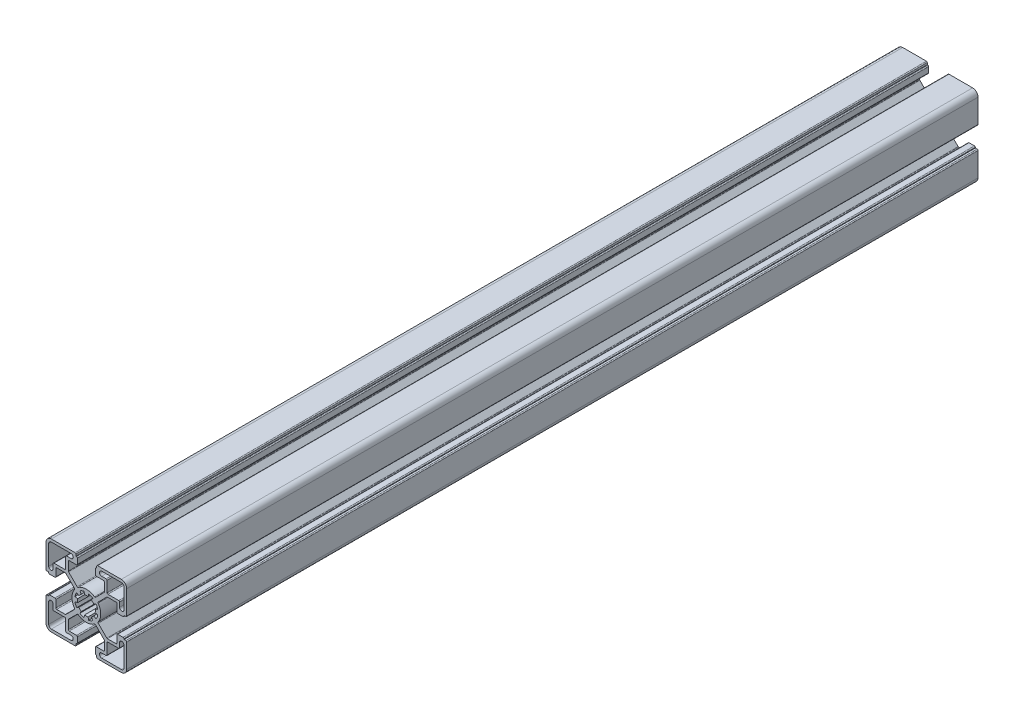
SolidWorks part; units mm, degrees
material "6063-O"
ref_plane "Front Plane" through (0, 0, 0) normal (0, 0, 1) x (1, 0, 0)
ref_plane "Top Plane" through (0, 0, 0) normal (0, 1, 0) x (1, 0, 0)
ref_plane "Right Plane" through (0, 0, 0) normal (1, 0, 0) x (0, 0, -1)
sketch "Sketch1" plane through (0, 0, 0) normal (0, 0, 1) x (1, 0, 0)
  line L0 (0, 22.5) -> (0, -22.5) construction
  line L1 (22.5, 0) -> (-22.5, 0) construction
  line L2 (-5.8, 22.5) -> (5.8, 22.5) construction
  line L3 (-5, 21) -> (5, 21) construction
  line L4 (-10.05, 10.05) -> (10.05, 10.05) construction
  line L5 (0, 0) -> (-10.05, 10.05) construction
  circle A0 centre (0, 0) radius 5 construction
  point P4 (0, 0)
  point P8 (0, 0)
  point P10 (0, 8)
  point P14 (0, 22.5)
  point P17 (0, 21)
  point P19 (0, 10.05)
sketch "Sketch2" plane through (0, 0, 0) normal (1, 0, 0) x (0, 0, -1)
  line L0 (152.4, 0) -> (-152.4, 0) construction
  point P4 (0, 0)
  dimension "D1" = 304.8
sketch "Sketch3" plane through (0, 0, 0) normal (0, 0, 1) x (1, 0, 0)
  line L5 (-21, 8.5375) -> (-21, 19.5)
  line L9 (0, 0) -> (-22.5, 22.5) construction
  line L10 (-11.55, -10.05) -> (-6.3569, -4.8569)
  line L11 (-19.5, 21) -> (-8.5375, 21)
  line L38 (-5.8, 22.5) -> (-5.8, 21)
  line L46 (-5.8, 21) -> (-5, 21)
  line L62 (-5, 21) -> (-5, 17.025)
  line L74 (-5, 17.025) -> (-10.05, 17.025)
  line L76 (-10.05, 17.025) -> (-10.05, 11.55)
  line L77 (-10.05, 11.55) -> (-4.8569, 6.3569)
  line L78 (-18.525, 8.5375) -> (-18.525, 11.55)
  line L79 (-10.05, 17.025) -> (-10.05, 22.5) construction
  line L80 (0, 22.5) -> (0, -22.5) construction
  line L81 (-5.8, 22.5) -> (5.8, 22.5) construction
  line L82 (10.05, 11.55) -> (4.8569, 6.3569)
  line L83 (10.05, 17.025) -> (10.05, 11.55)
  line L84 (5, 17.025) -> (10.05, 17.025)
  line L85 (5, 21) -> (5, 17.025)
  line L86 (5.8, 21) -> (5, 21)
  line L87 (5.8, 22.5) -> (5.8, 21)
  line L88 (-22.5, -5.8) -> (-21, -5.8)
  line L89 (-21, -5.8) -> (-21, -5)
  line L90 (-21, -5) -> (-17.025, -5)
  line L91 (-17.025, -5) -> (-17.025, -10.05)
  line L92 (-17.025, -10.05) -> (-11.55, -10.05)
  line L93 (-11.55, -10.05) -> (-6.3569, -4.8569)
  line L94 (-11.55, 10.05) -> (-6.3569, 4.8569)
  line L95 (-17.025, 10.05) -> (-11.55, 10.05)
  line L96 (-17.025, 5) -> (-17.025, 10.05)
  line L97 (-21, 5) -> (-17.025, 5)
  line L98 (-21, 5.8) -> (-21, 5)
  line L99 (-22.5, 5.8) -> (-21, 5.8)
  line L100 (-22.5, 5.8) -> (-22.5, 19.5)
  line L101 (-19.5, 22.5) -> (-5.8, 22.5)
  line L102 (-18.525, 11.55) -> (-11.55, 11.55)
  line L103 (-8.5375, 18.525) -> (-11.55, 18.525)
  line L104 (-11.55, 18.525) -> (-11.55, 11.55)
  line L108 (5.8, -22.5) -> (5.8, -21)
  line L113 (5.8, -21) -> (5, -21)
  line L117 (5.8, 22.5) -> (19.5, 22.5)
  line L118 (22.5, 19.5) -> (22.5, 5.8)
  line L119 (19.5, -22.5) -> (5.8, -22.5)
  line L120 (0, 0) -> (22.5, 0) construction
  line L121 (-22.5, -19.5) -> (-22.5, -5.8)
  line L136 (5, -21) -> (5, -17.025)
  line L137 (5, -17.025) -> (10.05, -17.025)
  line L138 (10.05, -17.025) -> (10.05, -11.55)
  line L139 (10.05, -11.55) -> (4.8569, -6.3569)
  line L140 (-10.05, -11.55) -> (-4.8569, -6.3569)
  line L141 (-10.05, -17.025) -> (-10.05, -11.55)
  line L142 (-5, -17.025) -> (-10.05, -17.025)
  line L143 (-5, -21) -> (-5, -17.025)
  line L144 (-5.8, -21) -> (-5, -21)
  line L145 (-5.8, -22.5) -> (-5.8, -21)
  line L146 (-5.8, -22.5) -> (-19.5, -22.5)
  line L147 (22.5, 5.8) -> (21, 5.8)
  line L148 (21, 5.8) -> (21, 5)
  line L149 (21, 5) -> (17.025, 5)
  line L150 (17.025, 5) -> (17.025, 10.05)
  line L151 (17.025, 10.05) -> (11.55, 10.05)
  line L152 (11.55, 10.05) -> (6.3569, 4.8569)
  line L153 (11.55, -10.05) -> (6.3569, -4.8569)
  line L154 (17.025, -10.05) -> (11.55, -10.05)
  line L155 (17.025, -5) -> (17.025, -10.05)
  line L156 (21, -5) -> (17.025, -5)
  line L157 (21, -5.8) -> (21, -5)
  line L158 (22.5, -5.8) -> (21, -5.8)
  line L159 (11.55, -10.05) -> (6.3569, -4.8569)
  line L160 (22.5, -5.8) -> (22.5, -19.5)
  line L161 (8.5375, 21) -> (19.5, 21)
  line L162 (21, 19.5) -> (21, 8.5375)
  line L163 (8.5375, 18.525) -> (11.55, 18.525)
  line L164 (11.55, 18.525) -> (11.55, 11.55)
  line L165 (18.525, 8.5375) -> (18.525, 11.55)
  line L166 (18.525, 11.55) -> (11.55, 11.55)
  line L167 (21, -8.5375) -> (21, -19.5)
  line L168 (19.5, -21) -> (8.5375, -21)
  line L169 (18.525, -8.5375) -> (18.525, -11.55)
  line L170 (18.525, -11.55) -> (11.55, -11.55)
  line L171 (8.5375, -18.525) -> (11.55, -18.525)
  line L172 (11.55, -18.525) -> (11.55, -11.55)
  line L173 (-8.5375, -21) -> (-19.5, -21)
  line L174 (-21, -19.5) -> (-21, -8.5375)
  line L175 (-8.5375, -18.525) -> (-11.55, -18.525)
  line L176 (-11.55, -18.525) -> (-11.55, -11.55)
  line L177 (-18.525, -8.5375) -> (-18.525, -11.55)
  line L178 (-18.525, -11.55) -> (-11.55, -11.55)
  line L179 (0, 0) -> (-11.55, 11.55) construction
  line L180 (0, 0) -> (11.55, 11.55) construction
  arc A2 (-21, 19.5) -> (-19.5, 21) centre (-19.5, 19.5) cw
  arc A73 (-4.8569, 6.3569) -> (4.8569, 6.3569) centre (0, 0) cw
  arc A74 (-6.3569, 4.8569) -> (-6.3569, -4.8569) centre (0, 0) ccw
  arc A75 (-19.5, 22.5) -> (-22.5, 19.5) centre (-19.5, 19.5) ccw
  arc A76 (-21, 8.5375) -> (-18.525, 8.5375) centre (-19.7625, 8.5375) ccw
  arc A77 (-8.5375, 21) -> (-8.5375, 18.525) centre (-8.5375, 19.7625) cw
  arc A80 (19.5, 22.5) -> (22.5, 19.5) centre (19.5, 19.5) cw
  arc A81 (22.5, -19.5) -> (19.5, -22.5) centre (19.5, -19.5) cw
  arc A82 (-19.5, -22.5) -> (-22.5, -19.5) centre (-19.5, -19.5) cw
  circle A88 centre (0, 0) radius 5 construction
  circle A89 centre (0, 0) radius 5
  arc A90 (-4.8569, -6.3569) -> (4.8569, -6.3569) centre (0, 0) ccw
  arc A91 (19.5, 21) -> (21, 19.5) centre (19.5, 19.5) cw
  arc A92 (6.3569, 4.8569) -> (6.3569, -4.8569) centre (0, 0) cw
  arc A93 (8.5375, 21) -> (8.5375, 18.525) centre (8.5375, 19.7625) ccw
  arc A94 (21, 8.5375) -> (18.525, 8.5375) centre (19.7625, 8.5375) cw
  arc A95 (21, -19.5) -> (19.5, -21) centre (19.5, -19.5) cw
  arc A96 (21, -8.5375) -> (18.525, -8.5375) centre (19.7625, -8.5375) ccw
  arc A97 (8.5375, -21) -> (8.5375, -18.525) centre (8.5375, -19.7625) cw
  arc A98 (-19.5, -21) -> (-21, -19.5) centre (-19.5, -19.5) cw
  arc A99 (-8.5375, -21) -> (-8.5375, -18.525) centre (-8.5375, -19.7625) ccw
  arc A100 (-21, -8.5375) -> (-18.525, -8.5375) centre (-19.7625, -8.5375) cw
  point P54 (-14.2875, 10.05)
  dimension "D2" = 3
  dimension "D3" = 1.5
  dimension "D4" = 1.5
  dimension "D5" = 1.5
  dimension "D6" = 90
  dimension "D1" = 4
extrude "Boss-Extrude1" add sketch "Sketch3" along normal up to vertex (152.4 mm away) and the other way up to vertex (152.4 mm away) contours A92 L152 L151 L150 L149 L148 L147 L118 A80 L117 L87 L86 L85 L84 L83 L82 A73 L77 L76 L74 L62 L46 L38 L101 A75 L100 L99 L98 L97 L96 L95 L94 A74 L10 L92 L91 L90 L89 L88 L121 A82 L146 L145 L144 L143 L142 L141 L140 A90 L139 L138 up to point (0, 0, 152.4) other way up to point (0, 0, -152.4)
fillet "Fillet1" radius 0.5 58 edges at (5, 21, 0) (5.8, 22.5, 0) (-5.8, 22.5, 0) (-5, 21, 0) (-10.05, 17.025, 0) (-5, 17.025, 0) (5, 17.025, 0) (-22.5, -5.8, 0) (-21, -5, 0) (-17.025, -5, 0) (-17.025, -10.05, 0) (-11.55, -10.05, 0) (-6.3569, -4.8569, 0) (-6.3569, 4.8569, 0) (-11.55, 10.05, 0) (-17.025, 10.05, 0) (-17.025, 5, 0) (-22.5, 5.8, 0) (-21, 5, 0) (-18.525, 11.55, 0) (-11.55, 11.55, 0) (-11.55, 18.525, 0) (4.8569, 6.3569, 0) (-4.8569, 6.3569, 0) (-10.05, 11.55, 0) (10.05, 17.025, 0) (10.05, 11.55, 0) (22.5, -5.8, 0) (21, -5, 0) (17.025, -5, 0) (17.025, -10.05, 0) (6.3569, 4.8569, 0) (11.55, 10.05, 0) (22.5, 5.8, 0) (21, 5, 0) (17.025, 5, 0) (4.8569, -6.3569, 0) (11.55, -11.55, 0) (-11.55, -11.55, 0) (18.525, -11.55, 0) (11.55, -18.525, 0) (10.05, -17.025, 0) (5, -17.025, 0) (5, -21, 0) (5.8, -22.5, 0) (-5.8, -22.5, 0) (-5, -21, 0) (-5, -17.025, 0) (-10.05, -17.025, 0) (-11.55, -18.525, 0) (11.55, 18.525, 0) (18.525, 11.55, 0) (11.55, 11.55, 0) (11.55, -10.05, 0) (6.3569, -4.8569, 0) (-4.8569, -6.3569, 0) (10.05, -11.55, 0) (-10.05, -11.55, 0)
sketch "Sketch4" plane through (0, 0, 152.4) normal (0, 0, 1) x (1, 0, 0)
  line L0 (-1.2681, 6.3751) -> (-0.9755, 4.9039)
  line L1 (0, 0) -> (0, 8) construction
  line L2 (-3.6112, 5.4046) -> (-2.7779, 4.1573)
  line L3 (1.2681, 6.3751) -> (0.9755, 4.9039)
  line L4 (3.6112, 5.4046) -> (2.7779, 4.1573)
  line L5 (5.4046, 3.6112) -> (4.1573, 2.7779)
  line L6 (6.3751, 1.2681) -> (4.9039, 0.9755)
  line L7 (6.3751, -1.2681) -> (4.9039, -0.9755)
  line L8 (5.4046, -3.6112) -> (4.1573, -2.7779)
  line L9 (3.6112, -5.4046) -> (2.7779, -4.1573)
  line L10 (1.2681, -6.3751) -> (0.9755, -4.9039)
  line L11 (-1.2681, -6.3751) -> (-0.9755, -4.9039)
  line L12 (-3.6112, -5.4046) -> (-2.7779, -4.1573)
  line L13 (-5.4046, -3.6112) -> (-4.1573, -2.7779)
  line L14 (-6.3751, -1.2681) -> (-4.9039, -0.9755)
  line L15 (-6.3751, 1.2681) -> (-4.9039, 0.9755)
  line L16 (-5.4046, 3.6112) -> (-4.1573, 2.7779)
  line L17 (0, 0) -> (-0.9755, 4.9039) construction
  line L18 (0, 0) -> (2.7779, 4.1573) construction
  arc A0 (-1.2681, 6.3751) -> (-3.6112, 5.4046) centre (0, 0) ccw
  circle A1 centre (0, 0) radius 5 construction
  arc A2 (-0.9755, 4.9039) -> (-2.7779, 4.1573) centre (0, 0) ccw
  arc A4 (2.7779, 4.1573) -> (0.9755, 4.9039) centre (0, 0) ccw
  arc A5 (3.6112, 5.4046) -> (1.2681, 6.3751) centre (0, 0) ccw
  arc A6 (4.9039, 0.9755) -> (4.1573, 2.7779) centre (0, 0) ccw
  arc A7 (6.3751, 1.2681) -> (5.4046, 3.6112) centre (0, 0) ccw
  arc A8 (4.1573, -2.7779) -> (4.9039, -0.9755) centre (0, 0) ccw
  arc A9 (5.4046, -3.6112) -> (6.3751, -1.2681) centre (0, 0) ccw
  arc A10 (0.9755, -4.9039) -> (2.7779, -4.1573) centre (0, 0) ccw
  arc A11 (1.2681, -6.3751) -> (3.6112, -5.4046) centre (0, 0) ccw
  arc A12 (-2.7779, -4.1573) -> (-0.9755, -4.9039) centre (0, 0) ccw
  arc A13 (-3.6112, -5.4046) -> (-1.2681, -6.3751) centre (0, 0) ccw
  arc A14 (-4.9039, -0.9755) -> (-4.1573, -2.7779) centre (0, 0) ccw
  arc A15 (-6.3751, -1.2681) -> (-5.4046, -3.6112) centre (0, 0) ccw
  arc A16 (-4.1573, 2.7779) -> (-4.9039, 0.9755) centre (0, 0) ccw
  arc A17 (-5.4046, 3.6112) -> (-6.3751, 1.2681) centre (0, 0) ccw
  dimension "D1" = 1.5
  dimension "D2" = 22.5
  dimension "D5" = 45
  dimension "D4" = 8
extrude "Cut-Extrude1" cut sketch "Sketch4" against normal through all
sketch "Sketch5" plane through (0, 0, 152.4) normal (0, 0, 1) x (1, 0, 0)
  line L6 (-11.55, -18.025) -> (-11.55, -12.05)
  line L7 (-8.5375, -18.525) -> (-11.05, -18.525)
  line L8 (-19.5, -21) -> (-8.5375, -21)
  line L9 (-21, -8.5375) -> (-21, -19.5)
  line L10 (-18.525, -11.55) -> (-18.525, -8.5375)
  line L11 (-12.05, -11.55) -> (-18.525, -11.55)
  line L12 (-11.55, -18.025) -> (-11.55, -12.05)
  line L13 (-8.5375, -18.525) -> (-11.05, -18.525)
  line L14 (-19.5, -21) -> (-8.5375, -21)
  line L15 (-21, -8.5375) -> (-21, -19.5)
  line L16 (-0.9755, 4.9039) -> (-1.2681, 6.3751)
  line L17 (1.2681, 6.3751) -> (0.9755, 4.9039)
  line L18 (2.7779, 4.1573) -> (3.6112, 5.4046)
  line L19 (5.4046, 3.6112) -> (4.1573, 2.7779)
  line L20 (4.9039, 0.9755) -> (6.3751, 1.2681)
  line L21 (6.3751, -1.2681) -> (4.9039, -0.9755)
  line L22 (4.1573, -2.7779) -> (5.4046, -3.6112)
  line L23 (3.6112, -5.4046) -> (2.7779, -4.1573)
  line L24 (0.9755, -4.9039) -> (1.2681, -6.3751)
  line L25 (-1.2681, -6.3751) -> (-0.9755, -4.9039)
  line L26 (-2.7779, -4.1573) -> (-3.6112, -5.4046)
  line L27 (-5.4046, -3.6112) -> (-4.1573, -2.7779)
  line L28 (-4.9039, -0.9755) -> (-6.3751, -1.2681)
  line L29 (-6.3751, 1.2681) -> (-4.9039, 0.9755)
  line L30 (-4.1573, 2.7779) -> (-5.4046, 3.6112)
  line L31 (-3.6112, 5.4046) -> (-2.7779, 4.1573)
  line L32 (-0.9755, 4.9039) -> (-1.2681, 6.3751)
  line L33 (1.2681, 6.3751) -> (0.9755, 4.9039)
  line L34 (2.7779, 4.1573) -> (3.6112, 5.4046)
  line L35 (5.4046, 3.6112) -> (4.1573, 2.7779)
  line L36 (4.9039, 0.9755) -> (6.3751, 1.2681)
  line L37 (6.3751, -1.2681) -> (4.9039, -0.9755)
  line L38 (4.1573, -2.7779) -> (5.4046, -3.6112)
  line L39 (3.6112, -5.4046) -> (2.7779, -4.1573)
  line L40 (0.9755, -4.9039) -> (1.2681, -6.3751)
  line L41 (-1.2681, -6.3751) -> (-0.9755, -4.9039)
  line L42 (-2.7779, -4.1573) -> (-3.6112, -5.4046)
  line L43 (-5.4046, -3.6112) -> (-4.1573, -2.7779)
  line L44 (-4.9039, -0.9755) -> (-6.3751, -1.2681)
  line L45 (-6.3751, 1.2681) -> (-4.9039, 0.9755)
  line L46 (-4.1573, 2.7779) -> (-5.4046, 3.6112)
  line L47 (-3.6112, 5.4046) -> (-2.7779, 4.1573)
  line L48 (-18.525, -11.55) -> (-18.525, -8.5375)
  line L49 (-12.05, -11.55) -> (-18.525, -11.55)
  line L50 (18.025, -11.55) -> (12.05, -11.55)
  line L51 (18.525, -8.5375) -> (18.525, -11.05)
  line L52 (21, -19.5) -> (21, -8.5375)
  line L53 (8.5375, -21) -> (19.5, -21)
  line L54 (11.05, -18.525) -> (8.5375, -18.525)
  line L55 (11.55, -12.05) -> (11.55, -18.025)
  line L56 (22.5, -19.5) -> (22.5, -6.3)
  line L57 (22, -5.8) -> (21, -5.8)
  line L58 (21, -5.8) -> (21, -5.5)
  line L59 (20.5, -5) -> (17.525, -5)
  line L60 (17.025, -5.5) -> (17.025, -9.55)
  line L61 (16.525, -10.05) -> (11.7571, -10.05)
  line L62 (11.4036, -9.9036) -> (6.6582, -5.1582)
  line L63 (6.6582, 5.1582) -> (11.4036, 9.9036)
  line L64 (11.7571, 10.05) -> (17.025, 10.05)
  line L65 (17.025, 10.05) -> (17.025, 5.5)
  line L66 (17.525, 5) -> (20.5, 5)
  line L67 (21, 5.5) -> (21, 5.8)
  line L68 (21, 5.8) -> (22, 5.8)
  line L69 (22.5, 6.3) -> (22.5, 19.5)
  line L70 (19.5, 22.5) -> (6.3, 22.5)
  line L71 (5.8, 22) -> (5.8, 21)
  line L72 (5.8, 21) -> (5.5, 21)
  line L73 (5, 20.5) -> (5, 17.525)
  line L74 (5.5, 17.025) -> (9.55, 17.025)
  line L75 (10.05, 16.525) -> (10.05, 11.7571)
  line L76 (9.9036, 11.4036) -> (5.1582, 6.6582)
  line L77 (-5.1582, 6.6582) -> (-9.9036, 11.4036)
  line L78 (-10.05, 11.7571) -> (-10.05, 16.525)
  line L79 (-9.55, 17.025) -> (-5.5, 17.025)
  line L80 (-5, 17.525) -> (-5, 20.5)
  line L81 (-5.5, 21) -> (-5.8, 21)
  line L82 (-5.8, 21) -> (-5.8, 22)
  line L83 (-6.3, 22.5) -> (-19.5, 22.5)
  line L84 (-22.5, 19.5) -> (-22.5, 6.3)
  line L85 (-22, 5.8) -> (-21, 5.8)
  line L86 (-21, 5.8) -> (-21, 5.5)
  line L87 (-20.5, 5) -> (-17.525, 5)
  line L88 (-17.025, 5.5) -> (-17.025, 9.55)
  line L89 (-16.525, 10.05) -> (-11.7571, 10.05)
  line L90 (-11.4036, 9.9036) -> (-6.6582, 5.1582)
  line L91 (-6.6582, -5.1582) -> (-11.4036, -9.9036)
  line L92 (-11.7571, -10.05) -> (-16.525, -10.05)
  line L93 (-17.025, -9.55) -> (-17.025, -5.5)
  line L94 (-17.525, -5) -> (-20.5, -5)
  line L95 (-21, -5.5) -> (-21, -5.8)
  line L96 (-21, -5.8) -> (-22, -5.8)
  line L97 (-22.5, -6.3) -> (-22.5, -19.5)
  line L98 (-19.5, -22.5) -> (-6.3, -22.5)
  line L99 (-5.8, -22) -> (-5.8, -21)
  line L100 (-5.8, -21) -> (-5.5, -21)
  line L101 (-5, -20.5) -> (-5, -17.525)
  line L102 (-5.5, -17.025) -> (-9.55, -17.025)
  line L103 (-10.05, -16.525) -> (-10.05, -11.7571)
  line L104 (-9.9036, -11.4036) -> (-5.1582, -6.6582)
  line L105 (5.1582, -6.6582) -> (9.9036, -11.4036)
  line L106 (10.05, -11.7571) -> (10.05, -16.525)
  line L107 (9.55, -17.025) -> (5.5, -17.025)
  line L108 (5, -17.525) -> (5, -20.5)
  line L109 (5.5, -21) -> (5.8, -21)
  line L110 (5.8, -21) -> (5.8, -22)
  line L111 (6.3, -22.5) -> (19.5, -22.5)
  line L112 (22.5, -19.5) -> (22.5, -6.3)
  line L113 (22, -5.8) -> (21, -5.8)
  line L114 (21, -5.8) -> (21, -5.5)
  line L115 (20.5, -5) -> (17.525, -5)
  line L116 (17.025, -5.5) -> (17.025, -9.55)
  line L117 (16.525, -10.05) -> (11.7571, -10.05)
  line L118 (11.4036, -9.9036) -> (6.6582, -5.1582)
  line L119 (6.6582, 5.1582) -> (11.4036, 9.9036)
  line L120 (11.7571, 10.05) -> (17.025, 10.05)
  line L121 (17.025, 10.05) -> (17.025, 5.5)
  line L122 (17.525, 5) -> (20.5, 5)
  line L123 (21, 5.5) -> (21, 5.8)
  line L124 (21, 5.8) -> (22, 5.8)
  line L125 (22.5, 6.3) -> (22.5, 19.5)
  line L126 (19.5, 22.5) -> (6.3, 22.5)
  line L127 (5.8, 22) -> (5.8, 21)
  line L128 (5.8, 21) -> (5.5, 21)
  line L129 (5, 20.5) -> (5, 17.525)
  line L130 (5.5, 17.025) -> (9.55, 17.025)
  line L131 (10.05, 16.525) -> (10.05, 11.7571)
  line L132 (9.9036, 11.4036) -> (5.1582, 6.6582)
  line L133 (-5.1582, 6.6582) -> (-9.9036, 11.4036)
  line L134 (-10.05, 11.7571) -> (-10.05, 16.525)
  line L135 (-9.55, 17.025) -> (-5.5, 17.025)
  line L136 (-5, 17.525) -> (-5, 20.5)
  line L137 (-5.5, 21) -> (-5.8, 21)
  line L138 (-5.8, 21) -> (-5.8, 22)
  line L139 (-6.3, 22.5) -> (-19.5, 22.5)
  line L140 (-22.5, 19.5) -> (-22.5, 6.3)
  line L141 (-22, 5.8) -> (-21, 5.8)
  line L142 (-21, 5.8) -> (-21, 5.5)
  line L143 (-20.5, 5) -> (-17.525, 5)
  line L144 (-17.025, 5.5) -> (-17.025, 9.55)
  line L145 (-16.525, 10.05) -> (-11.7571, 10.05)
  line L146 (-11.4036, 9.9036) -> (-6.6582, 5.1582)
  line L147 (-6.6582, -5.1582) -> (-11.4036, -9.9036)
  line L148 (-11.7571, -10.05) -> (-16.525, -10.05)
  line L149 (-17.025, -9.55) -> (-17.025, -5.5)
  line L150 (-17.525, -5) -> (-20.5, -5)
  line L151 (-21, -5.5) -> (-21, -5.8)
  line L152 (-21, -5.8) -> (-22, -5.8)
  line L153 (-22.5, -6.3) -> (-22.5, -19.5)
  line L154 (-19.5, -22.5) -> (-6.3, -22.5)
  line L155 (-5.8, -22) -> (-5.8, -21)
  line L156 (-5.8, -21) -> (-5.5, -21)
  line L157 (-5, -20.5) -> (-5, -17.525)
  line L158 (-5.5, -17.025) -> (-9.55, -17.025)
  line L159 (-10.05, -16.525) -> (-10.05, -11.7571)
  line L160 (-9.9036, -11.4036) -> (-5.1582, -6.6582)
  line L161 (5.1582, -6.6582) -> (9.9036, -11.4036)
  line L162 (10.05, -11.7571) -> (10.05, -16.525)
  line L163 (9.55, -17.025) -> (5.5, -17.025)
  line L164 (5, -17.525) -> (5, -20.5)
  line L165 (5.5, -21) -> (5.8, -21)
  line L166 (5.8, -21) -> (5.8, -22)
  line L167 (6.3, -22.5) -> (19.5, -22.5)
  line L168 (18.025, -11.55) -> (12.05, -11.55)
  line L169 (18.525, -8.5375) -> (18.525, -11.05)
  line L170 (21, -19.5) -> (21, -8.5375)
  line L171 (8.5375, -21) -> (19.5, -21)
  line L172 (11.05, -18.525) -> (8.5375, -18.525)
  line L173 (11.55, -12.05) -> (11.55, -18.025)
  line L174 (11.55, 18.025) -> (11.55, 12.05)
  line L175 (8.5375, 18.525) -> (11.05, 18.525)
  line L176 (19.5, 21) -> (8.5375, 21)
  line L177 (21, 8.5375) -> (21, 19.5)
  line L178 (18.525, 11.05) -> (18.525, 8.5375)
  line L179 (12.05, 11.55) -> (18.025, 11.55)
  line L180 (11.55, 18.025) -> (11.55, 12.05)
  line L181 (8.5375, 18.525) -> (11.05, 18.525)
  line L182 (19.5, 21) -> (8.5375, 21)
  line L183 (21, 8.5375) -> (21, 19.5)
  line L184 (18.525, 11.05) -> (18.525, 8.5375)
  line L185 (12.05, 11.55) -> (18.025, 11.55)
  line L186 (-18.025, 11.55) -> (-12.05, 11.55)
  line L187 (-18.525, 8.5375) -> (-18.525, 11.05)
  line L188 (-21, 19.5) -> (-21, 8.5375)
  line L189 (-8.5375, 21) -> (-19.5, 21)
  line L190 (-11.05, 18.525) -> (-8.5375, 18.525)
  line L191 (-11.55, 12.05) -> (-11.55, 18.025)
  line L192 (-18.025, 11.55) -> (-12.05, 11.55)
  line L193 (-18.525, 8.5375) -> (-18.525, 11.05)
  line L194 (-21, 19.5) -> (-21, 8.5375)
  line L195 (-8.5375, 21) -> (-19.5, 21)
  line L196 (-11.05, 18.525) -> (-8.5375, 18.525)
  line L197 (-11.55, 12.05) -> (-11.55, 18.025)
  arc A5 (-11.55, -18.025) -> (-11.05, -18.525) centre (-11.05, -18.025) ccw
  arc A6 (-8.5375, -21) -> (-8.5375, -18.525) centre (-8.5375, -19.7625) ccw
  arc A7 (-21, -19.5) -> (-19.5, -21) centre (-19.5, -19.5) ccw
  arc A8 (-18.525, -8.5375) -> (-21, -8.5375) centre (-19.7625, -8.5375) ccw
  arc A9 (-11.55, -12.05) -> (-12.05, -11.55) centre (-12.05, -12.05) ccw
  arc A10 (-11.55, -18.025) -> (-11.05, -18.525) centre (-11.05, -18.025) ccw
  arc A11 (-8.5375, -21) -> (-8.5375, -18.525) centre (-8.5375, -19.7625) ccw
  arc A12 (-21, -19.5) -> (-19.5, -21) centre (-19.5, -19.5) ccw
  arc A13 (-18.525, -8.5375) -> (-21, -8.5375) centre (-19.7625, -8.5375) ccw
  arc A14 (-11.55, -12.05) -> (-12.05, -11.55) centre (-12.05, -12.05) ccw
  arc A16 (0.9755, 4.9039) -> (-0.9755, 4.9039) centre (0, 0) ccw
  arc A17 (3.6112, 5.4046) -> (1.2681, 6.3751) centre (0, 0) ccw
  arc A18 (4.1573, 2.7779) -> (2.7779, 4.1573) centre (0, 0) ccw
  arc A19 (6.3751, 1.2681) -> (5.4046, 3.6112) centre (0, 0) ccw
  arc A20 (4.9039, -0.9755) -> (4.9039, 0.9755) centre (0, 0) ccw
  arc A21 (5.4046, -3.6112) -> (6.3751, -1.2681) centre (0, 0) ccw
  arc A22 (2.7779, -4.1573) -> (4.1573, -2.7779) centre (0, 0) ccw
  arc A23 (1.2681, -6.3751) -> (3.6112, -5.4046) centre (0, 0) ccw
  arc A24 (-0.9755, -4.9039) -> (0.9755, -4.9039) centre (0, 0) ccw
  arc A25 (-3.6112, -5.4046) -> (-1.2681, -6.3751) centre (0, 0) ccw
  arc A26 (-4.1573, -2.7779) -> (-2.7779, -4.1573) centre (0, 0) ccw
  arc A27 (-6.3751, -1.2681) -> (-5.4046, -3.6112) centre (0, 0) ccw
  arc A28 (-4.9039, 0.9755) -> (-4.9039, -0.9755) centre (0, 0) ccw
  arc A29 (-5.4046, 3.6112) -> (-6.3751, 1.2681) centre (0, 0) ccw
  arc A30 (-2.7779, 4.1573) -> (-4.1573, 2.7779) centre (0, 0) ccw
  arc A31 (-1.2681, 6.3751) -> (-3.6112, 5.4046) centre (0, 0) ccw
  arc A32 (0.9755, 4.9039) -> (-0.9755, 4.9039) centre (0, 0) ccw
  arc A33 (3.6112, 5.4046) -> (1.2681, 6.3751) centre (0, 0) ccw
  arc A34 (4.1573, 2.7779) -> (2.7779, 4.1573) centre (0, 0) ccw
  arc A35 (6.3751, 1.2681) -> (5.4046, 3.6112) centre (0, 0) ccw
  arc A36 (4.9039, -0.9755) -> (4.9039, 0.9755) centre (0, 0) ccw
  arc A37 (5.4046, -3.6112) -> (6.3751, -1.2681) centre (0, 0) ccw
  arc A38 (2.7779, -4.1573) -> (4.1573, -2.7779) centre (0, 0) ccw
  arc A39 (1.2681, -6.3751) -> (3.6112, -5.4046) centre (0, 0) ccw
  arc A40 (-0.9755, -4.9039) -> (0.9755, -4.9039) centre (0, 0) ccw
  arc A41 (-3.6112, -5.4046) -> (-1.2681, -6.3751) centre (0, 0) ccw
  arc A42 (-4.1573, -2.7779) -> (-2.7779, -4.1573) centre (0, 0) ccw
  arc A43 (-6.3751, -1.2681) -> (-5.4046, -3.6112) centre (0, 0) ccw
  arc A44 (-4.9039, 0.9755) -> (-4.9039, -0.9755) centre (0, 0) ccw
  arc A45 (-5.4046, 3.6112) -> (-6.3751, 1.2681) centre (0, 0) ccw
  arc A46 (-2.7779, 4.1573) -> (-4.1573, 2.7779) centre (0, 0) ccw
  arc A47 (-1.2681, 6.3751) -> (-3.6112, 5.4046) centre (0, 0) ccw
  arc A48 (18.025, -11.55) -> (18.525, -11.05) centre (18.025, -11.05) ccw
  arc A49 (21, -8.5375) -> (18.525, -8.5375) centre (19.7625, -8.5375) ccw
  arc A50 (19.5, -21) -> (21, -19.5) centre (19.5, -19.5) ccw
  arc A51 (8.5375, -18.525) -> (8.5375, -21) centre (8.5375, -19.7625) ccw
  arc A52 (11.05, -18.525) -> (11.55, -18.025) centre (11.05, -18.025) ccw
  arc A53 (12.05, -11.55) -> (11.55, -12.05) centre (12.05, -12.05) ccw
  arc A54 (18.025, -11.55) -> (18.525, -11.05) centre (18.025, -11.05) ccw
  arc A55 (22.5, -6.3) -> (22, -5.8) centre (22, -6.3) ccw
  arc A56 (21, -5.5) -> (20.5, -5) centre (20.5, -5.5) ccw
  arc A57 (17.525, -5) -> (17.025, -5.5) centre (17.525, -5.5) ccw
  arc A58 (16.525, -10.05) -> (17.025, -9.55) centre (16.525, -9.55) ccw
  arc A59 (11.4036, -9.9036) -> (11.7571, -10.05) centre (11.7571, -9.55) ccw
  arc A60 (6.5993, -4.522) -> (6.6582, -5.1582) centre (7.0118, -4.8047) ccw
  arc A61 (6.5993, -4.522) -> (6.5993, 4.522) centre (0, 0) ccw
  arc A62 (6.6582, 5.1582) -> (6.5993, 4.522) centre (7.0118, 4.8047) ccw
  arc A63 (11.7571, 10.05) -> (11.4036, 9.9036) centre (11.7571, 9.55) ccw
  arc A64 (17.025, 5.5) -> (17.525, 5) centre (17.525, 5.5) ccw
  arc A65 (20.5, 5) -> (21, 5.5) centre (20.5, 5.5) ccw
  arc A66 (22, 5.8) -> (22.5, 6.3) centre (22, 6.3) ccw
  arc A67 (22.5, 19.5) -> (19.5, 22.5) centre (19.5, 19.5) ccw
  arc A68 (6.3, 22.5) -> (5.8, 22) centre (6.3, 22) ccw
  arc A69 (5.5, 21) -> (5, 20.5) centre (5.5, 20.5) ccw
  arc A70 (5, 17.525) -> (5.5, 17.025) centre (5.5, 17.525) ccw
  arc A71 (10.05, 16.525) -> (9.55, 17.025) centre (9.55, 16.525) ccw
  arc A72 (9.9036, 11.4036) -> (10.05, 11.7571) centre (9.55, 11.7571) ccw
  arc A73 (4.522, 6.5993) -> (5.1582, 6.6582) centre (4.8047, 7.0118) ccw
  arc A74 (4.522, 6.5993) -> (-4.522, 6.5993) centre (0, 0) ccw
  arc A75 (-5.1582, 6.6582) -> (-4.522, 6.5993) centre (-4.8047, 7.0118) ccw
  arc A76 (-10.05, 11.7571) -> (-9.9036, 11.4036) centre (-9.55, 11.7571) ccw
  arc A77 (-9.55, 17.025) -> (-10.05, 16.525) centre (-9.55, 16.525) ccw
  arc A78 (-5.5, 17.025) -> (-5, 17.525) centre (-5.5, 17.525) ccw
  arc A79 (-5, 20.5) -> (-5.5, 21) centre (-5.5, 20.5) ccw
  arc A80 (-5.8, 22) -> (-6.3, 22.5) centre (-6.3, 22) ccw
  arc A81 (-19.5, 22.5) -> (-22.5, 19.5) centre (-19.5, 19.5) ccw
  arc A82 (-22.5, 6.3) -> (-22, 5.8) centre (-22, 6.3) ccw
  arc A83 (-21, 5.5) -> (-20.5, 5) centre (-20.5, 5.5) ccw
  arc A84 (-17.525, 5) -> (-17.025, 5.5) centre (-17.525, 5.5) ccw
  arc A85 (-16.525, 10.05) -> (-17.025, 9.55) centre (-16.525, 9.55) ccw
  arc A86 (-11.4036, 9.9036) -> (-11.7571, 10.05) centre (-11.7571, 9.55) ccw
  arc A87 (-6.5993, 4.522) -> (-6.6582, 5.1582) centre (-7.0118, 4.8047) ccw
  arc A88 (-6.5993, 4.522) -> (-6.5993, -4.522) centre (0, 0) ccw
  arc A89 (-6.6582, -5.1582) -> (-6.5993, -4.522) centre (-7.0118, -4.8047) ccw
  arc A90 (-11.7571, -10.05) -> (-11.4036, -9.9036) centre (-11.7571, -9.55) ccw
  arc A91 (-17.025, -9.55) -> (-16.525, -10.05) centre (-16.525, -9.55) ccw
  arc A92 (-17.025, -5.5) -> (-17.525, -5) centre (-17.525, -5.5) ccw
  arc A93 (-20.5, -5) -> (-21, -5.5) centre (-20.5, -5.5) ccw
  arc A94 (-22, -5.8) -> (-22.5, -6.3) centre (-22, -6.3) ccw
  arc A95 (-22.5, -19.5) -> (-19.5, -22.5) centre (-19.5, -19.5) ccw
  arc A96 (-6.3, -22.5) -> (-5.8, -22) centre (-6.3, -22) ccw
  arc A97 (-5.5, -21) -> (-5, -20.5) centre (-5.5, -20.5) ccw
  arc A98 (-5, -17.525) -> (-5.5, -17.025) centre (-5.5, -17.525) ccw
  arc A99 (-10.05, -16.525) -> (-9.55, -17.025) centre (-9.55, -16.525) ccw
  arc A100 (-9.9036, -11.4036) -> (-10.05, -11.7571) centre (-9.55, -11.7571) ccw
  arc A101 (-4.522, -6.5993) -> (-5.1582, -6.6582) centre (-4.8047, -7.0118) ccw
  arc A102 (-4.522, -6.5993) -> (4.522, -6.5993) centre (0, 0) ccw
  arc A103 (5.1582, -6.6582) -> (4.522, -6.5993) centre (4.8047, -7.0118) ccw
  arc A104 (10.05, -11.7571) -> (9.9036, -11.4036) centre (9.55, -11.7571) ccw
  arc A105 (9.55, -17.025) -> (10.05, -16.525) centre (9.55, -16.525) ccw
  arc A106 (5.5, -17.025) -> (5, -17.525) centre (5.5, -17.525) ccw
  arc A107 (5, -20.5) -> (5.5, -21) centre (5.5, -20.5) ccw
  arc A108 (5.8, -22) -> (6.3, -22.5) centre (6.3, -22) ccw
  arc A109 (19.5, -22.5) -> (22.5, -19.5) centre (19.5, -19.5) ccw
  arc A110 (22.5, -6.3) -> (22, -5.8) centre (22, -6.3) ccw
  arc A111 (21, -5.5) -> (20.5, -5) centre (20.5, -5.5) ccw
  arc A112 (17.525, -5) -> (17.025, -5.5) centre (17.525, -5.5) ccw
  arc A113 (16.525, -10.05) -> (17.025, -9.55) centre (16.525, -9.55) ccw
  arc A114 (11.4036, -9.9036) -> (11.7571, -10.05) centre (11.7571, -9.55) ccw
  arc A115 (6.5993, -4.522) -> (6.6582, -5.1582) centre (7.0118, -4.8047) ccw
  arc A116 (6.5993, -4.522) -> (6.5993, 4.522) centre (0, 0) ccw
  arc A117 (6.6582, 5.1582) -> (6.5993, 4.522) centre (7.0118, 4.8047) ccw
  arc A118 (11.7571, 10.05) -> (11.4036, 9.9036) centre (11.7571, 9.55) ccw
  arc A119 (17.025, 5.5) -> (17.525, 5) centre (17.525, 5.5) ccw
  arc A120 (20.5, 5) -> (21, 5.5) centre (20.5, 5.5) ccw
  arc A121 (22, 5.8) -> (22.5, 6.3) centre (22, 6.3) ccw
  arc A122 (22.5, 19.5) -> (19.5, 22.5) centre (19.5, 19.5) ccw
  arc A123 (6.3, 22.5) -> (5.8, 22) centre (6.3, 22) ccw
  arc A124 (5.5, 21) -> (5, 20.5) centre (5.5, 20.5) ccw
  arc A125 (5, 17.525) -> (5.5, 17.025) centre (5.5, 17.525) ccw
  arc A126 (10.05, 16.525) -> (9.55, 17.025) centre (9.55, 16.525) ccw
  arc A127 (9.9036, 11.4036) -> (10.05, 11.7571) centre (9.55, 11.7571) ccw
  arc A128 (4.522, 6.5993) -> (5.1582, 6.6582) centre (4.8047, 7.0118) ccw
  arc A129 (4.522, 6.5993) -> (-4.522, 6.5993) centre (0, 0) ccw
  arc A130 (-5.1582, 6.6582) -> (-4.522, 6.5993) centre (-4.8047, 7.0118) ccw
  arc A131 (-10.05, 11.7571) -> (-9.9036, 11.4036) centre (-9.55, 11.7571) ccw
  arc A132 (-9.55, 17.025) -> (-10.05, 16.525) centre (-9.55, 16.525) ccw
  arc A133 (-5.5, 17.025) -> (-5, 17.525) centre (-5.5, 17.525) ccw
  arc A134 (-5, 20.5) -> (-5.5, 21) centre (-5.5, 20.5) ccw
  arc A135 (-5.8, 22) -> (-6.3, 22.5) centre (-6.3, 22) ccw
  arc A136 (-19.5, 22.5) -> (-22.5, 19.5) centre (-19.5, 19.5) ccw
  arc A137 (-22.5, 6.3) -> (-22, 5.8) centre (-22, 6.3) ccw
  arc A138 (-21, 5.5) -> (-20.5, 5) centre (-20.5, 5.5) ccw
  arc A139 (-17.525, 5) -> (-17.025, 5.5) centre (-17.525, 5.5) ccw
  arc A140 (-16.525, 10.05) -> (-17.025, 9.55) centre (-16.525, 9.55) ccw
  arc A141 (-11.4036, 9.9036) -> (-11.7571, 10.05) centre (-11.7571, 9.55) ccw
  arc A142 (-6.5993, 4.522) -> (-6.6582, 5.1582) centre (-7.0118, 4.8047) ccw
  arc A143 (-6.5993, 4.522) -> (-6.5993, -4.522) centre (0, 0) ccw
  arc A144 (-6.6582, -5.1582) -> (-6.5993, -4.522) centre (-7.0118, -4.8047) ccw
  arc A145 (-11.7571, -10.05) -> (-11.4036, -9.9036) centre (-11.7571, -9.55) ccw
  arc A146 (-17.025, -9.55) -> (-16.525, -10.05) centre (-16.525, -9.55) ccw
  arc A147 (-17.025, -5.5) -> (-17.525, -5) centre (-17.525, -5.5) ccw
  arc A148 (-20.5, -5) -> (-21, -5.5) centre (-20.5, -5.5) ccw
  arc A149 (-22, -5.8) -> (-22.5, -6.3) centre (-22, -6.3) ccw
  arc A150 (-22.5, -19.5) -> (-19.5, -22.5) centre (-19.5, -19.5) ccw
  arc A151 (-6.3, -22.5) -> (-5.8, -22) centre (-6.3, -22) ccw
  arc A152 (-5.5, -21) -> (-5, -20.5) centre (-5.5, -20.5) ccw
  arc A153 (-5, -17.525) -> (-5.5, -17.025) centre (-5.5, -17.525) ccw
  arc A154 (-10.05, -16.525) -> (-9.55, -17.025) centre (-9.55, -16.525) ccw
  arc A155 (-9.9036, -11.4036) -> (-10.05, -11.7571) centre (-9.55, -11.7571) ccw
  arc A156 (-4.522, -6.5993) -> (-5.1582, -6.6582) centre (-4.8047, -7.0118) ccw
  arc A157 (-4.522, -6.5993) -> (4.522, -6.5993) centre (0, 0) ccw
  arc A158 (5.1582, -6.6582) -> (4.522, -6.5993) centre (4.8047, -7.0118) ccw
  arc A159 (10.05, -11.7571) -> (9.9036, -11.4036) centre (9.55, -11.7571) ccw
  arc A160 (9.55, -17.025) -> (10.05, -16.525) centre (9.55, -16.525) ccw
  arc A161 (5.5, -17.025) -> (5, -17.525) centre (5.5, -17.525) ccw
  arc A162 (5, -20.5) -> (5.5, -21) centre (5.5, -20.5) ccw
  arc A163 (5.8, -22) -> (6.3, -22.5) centre (6.3, -22) ccw
  arc A164 (19.5, -22.5) -> (22.5, -19.5) centre (19.5, -19.5) ccw
  arc A165 (21, -8.5375) -> (18.525, -8.5375) centre (19.7625, -8.5375) ccw
  arc A166 (19.5, -21) -> (21, -19.5) centre (19.5, -19.5) ccw
  arc A167 (8.5375, -18.525) -> (8.5375, -21) centre (8.5375, -19.7625) ccw
  arc A168 (11.05, -18.525) -> (11.55, -18.025) centre (11.05, -18.025) ccw
  arc A169 (12.05, -11.55) -> (11.55, -12.05) centre (12.05, -12.05) ccw
  arc A170 (11.55, 18.025) -> (11.05, 18.525) centre (11.05, 18.025) ccw
  arc A171 (8.5375, 21) -> (8.5375, 18.525) centre (8.5375, 19.7625) ccw
  arc A172 (21, 19.5) -> (19.5, 21) centre (19.5, 19.5) ccw
  arc A173 (18.525, 8.5375) -> (21, 8.5375) centre (19.7625, 8.5375) ccw
  arc A174 (18.525, 11.05) -> (18.025, 11.55) centre (18.025, 11.05) ccw
  arc A175 (11.55, 12.05) -> (12.05, 11.55) centre (12.05, 12.05) ccw
  arc A176 (11.55, 18.025) -> (11.05, 18.525) centre (11.05, 18.025) ccw
  arc A177 (8.5375, 21) -> (8.5375, 18.525) centre (8.5375, 19.7625) ccw
  arc A178 (21, 19.5) -> (19.5, 21) centre (19.5, 19.5) ccw
  arc A179 (18.525, 8.5375) -> (21, 8.5375) centre (19.7625, 8.5375) ccw
  arc A180 (18.525, 11.05) -> (18.025, 11.55) centre (18.025, 11.05) ccw
  arc A181 (11.55, 12.05) -> (12.05, 11.55) centre (12.05, 12.05) ccw
  arc A182 (-18.025, 11.55) -> (-18.525, 11.05) centre (-18.025, 11.05) ccw
  arc A183 (-21, 8.5375) -> (-18.525, 8.5375) centre (-19.7625, 8.5375) ccw
  arc A184 (-19.5, 21) -> (-21, 19.5) centre (-19.5, 19.5) ccw
  arc A185 (-8.5375, 18.525) -> (-8.5375, 21) centre (-8.5375, 19.7625) ccw
  arc A186 (-11.05, 18.525) -> (-11.55, 18.025) centre (-11.05, 18.025) ccw
  arc A187 (-12.05, 11.55) -> (-11.55, 12.05) centre (-12.05, 12.05) ccw
  arc A188 (-18.025, 11.55) -> (-18.525, 11.05) centre (-18.025, 11.05) ccw
  arc A189 (-21, 8.5375) -> (-18.525, 8.5375) centre (-19.7625, 8.5375) ccw
  arc A190 (-19.5, 21) -> (-21, 19.5) centre (-19.5, 19.5) ccw
  arc A191 (-8.5375, 18.525) -> (-8.5375, 21) centre (-8.5375, 19.7625) ccw
  arc A192 (-11.05, 18.525) -> (-11.55, 18.025) centre (-11.05, 18.025) ccw
  arc A193 (-12.05, 11.55) -> (-11.55, 12.05) centre (-12.05, 12.05) ccw
  dimension "D1" = 0
  dimension "D2" = 0
  dimension "D3" = 0
  dimension "D4" = 0
  dimension "D5" = 0
  dimension "D6" = 0
extrude "Boss-Extrude2" add sketch "Sketch5" along normal blind 169.95
equation "\"D3@Sketch3\"=\"Wall@Sketch1\""
equation "\"D4@Sketch3\"=\"Wall@Sketch1\""
equation "\"D5@Sketch3\"=\"Wall@Sketch1\""
equation "\"D1@Sketch4\"=\"Wall@Sketch1\""
